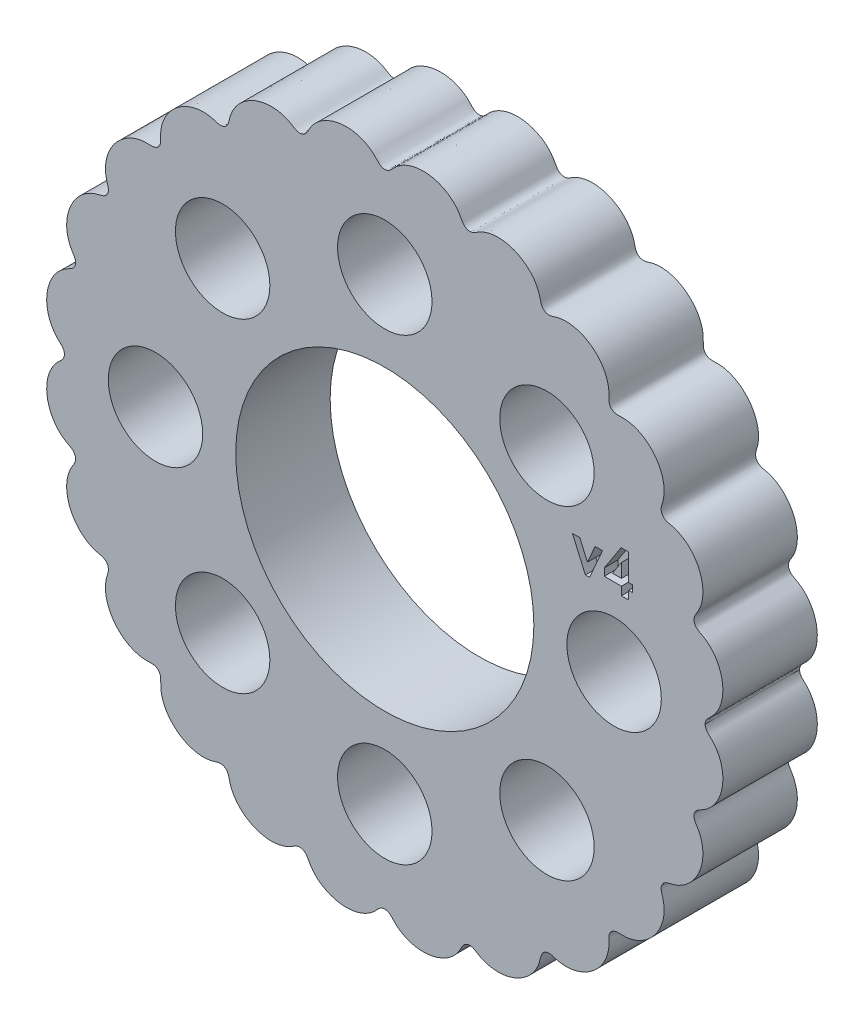
SolidWorks part; units mm, degrees
ref_plane "Plan de face" through (0, 0, 0) normal (0, 0, 1) x (1, 0, 0)
ref_plane "Plan de dessus" through (0, 0, 0) normal (0, 1, 0) x (1, 0, 0)
ref_plane "Plan de droite" through (0, 0, 0) normal (1, 0, 0) x (0, 0, -1)
sketch "Esquisse1" plane through (0, 0, 0) normal (0, 0, 1) x (1, 0, 0)
  line L0 (-1000, 0) -> (49000, 0) construction
  spline S0 degree 4 poles (22.9955, 6.6042) (22.9643, 6.5397) (22.914, 6.4032) (22.9023, 6.1862) (23.0214, 5.9244) (23.2219, 5.7605) (23.4288, 5.659) (23.6594, 5.5306) (23.9059, 5.3649) (24.1666, 5.1353) (24.4254, 4.835) (24.6422, 4.5029) (24.8162, 4.1468) (24.946, 3.7722) (25.0308, 3.385) (25.0698, 2.9906) (25.0624, 2.5943) (25.0079, 2.2017) (24.9068, 1.8224) (24.7781, 1.5066) (24.64, 1.2523) (24.5081, 1.0548) (24.3917, 0.9046) (24.2647, 0.7631) (24.1289, 0.6302) (24.012, 0.5251) (23.9248, 0.4355) (23.8688, 0.3622) (23.8363, 0.3122) (23.8082, 0.2597) (23.7852, 0.2044) (23.7697, 0.1547) (23.76, 0.1121) (23.7533, 0.0661) (23.7501, 0.0228) (23.7495, -0.004) (23.7513, -0.04) (23.7542, -0.0715) (23.7595, -0.1093) (23.7688, -0.1512) (23.7835, -0.1997) (23.8056, -0.2538) (23.8324, -0.3054) (23.8635, -0.3546) (23.9194, -0.4297) (24.009, -0.5227) (24.1313, -0.6322) (24.2737, -0.7721) (24.4392, -0.959) (24.6145, -1.2025) (24.7855, -1.5135) (24.9316, -1.8961) (25.0271, -2.299) (25.0708, -2.7153) (25.0622, -3.1311) (25.0033, -3.5401) (24.8958, -3.9363) (24.7419, -4.314) (24.5445, -4.6645) (24.307, -4.9822) (24.0331, -5.2614) (23.7654, -5.4667) (23.5164, -5.6129) (23.2956, -5.7243) (23.1195, -5.8363) (22.9763, -6.0087) (22.9044, -6.234) (22.925, -6.462) (23.0164, -6.6581) (23.1266, -6.8267) (23.2244, -6.9889) (23.3341, -7.1984) (23.4412, -7.4619) (23.5336, -7.7957) (23.5876, -8.2004) (23.5865, -8.623) (23.5267, -9.0558) (23.3808, -9.5868) (23.1436, -10.0885) (22.8209, -10.5434) (22.4327, -10.9196) (22.1006, -11.1627) (21.7948, -11.3267) (21.5321, -11.4304) (21.3065, -11.4954) (21.1232, -11.5381) (20.9306, -11.5808) (20.7385, -11.6689) (20.5325, -11.8672) (20.4495, -12.16) (20.5219, -12.4298) (20.6167, -12.7241) (20.6818, -13.0067) (20.7176, -13.3406) (20.7046, -13.7295) (20.6405, -14.1156) (20.5273, -14.4945) (20.3673, -14.8595) (20.1602, -15.2112) (19.9061, -15.5428) (19.6059, -15.8469) (19.261, -16.115) (18.8955, -16.3273) (18.5181, -16.4829) (18.1828, -16.5697) (17.9011, -16.6087) (17.6647, -16.6185) (17.4754, -16.6149) (17.2743, -16.6037) (17.0588, -16.6226) (16.851, -16.7187) (16.6918, -16.8937) (16.6141, -17.104) (16.6052, -17.3124) (16.6191, -17.5593) (16.617, -17.8481) (16.5731, -18.1826) (16.4683, -18.5594) (16.3118, -18.9239) (16.107, -19.2701) (15.8569, -19.5923) (15.5674, -19.8834) (15.2427, -20.1389) (14.8869, -20.3543) (14.5046, -20.5246) (14.1078, -20.6433) (13.7035, -20.7081) (13.2985, -20.7166) (12.9508, -20.673) (12.6603, -20.5981) (12.4161, -20.517) (12.2029, -20.4723) (11.9744, -20.5019) (11.768, -20.6211) (11.6281, -20.8042) (11.5602, -21.0112) (11.5084, -21.2632) (11.428, -21.5523) (11.2919, -21.8752) (11.082, -22.2216) (10.8237, -22.5394) (10.5226, -22.8236) (10.1839, -23.0696) (9.8195, -23.2701) (9.4358, -23.4235) (9.039, -23.5286) (8.6349, -23.5841) (8.2327, -23.5884) (7.8388, -23.5416) (7.4601, -23.444) (7.1484, -23.3148) (6.8973, -23.1723) (6.6904, -23.0367) (6.5054, -22.9402) (6.2844, -22.9024) (6.0534, -22.9528) (5.8662, -23.0846) (5.7421, -23.2618) (5.6512, -23.4416) (5.5596, -23.6073) (5.4331, -23.8072) (5.2584, -24.0316) (5.0155, -24.2786) (4.6921, -24.5276) (4.2308, -24.7924) (3.7121, -24.9769) (3.1672, -25.0695) (2.6142, -25.0665) (2.1723, -25.0046) (1.7597, -24.8871) (1.3831, -24.721) (1.0882, -24.5382) (0.867, -24.3625) (0.6979, -24.1997) (0.5693, -24.0623) (0.436, -23.9168) (0.2637, -23.7945) (-0.011, -23.7153) (-0.3061, -23.7898) (-0.5036, -23.9874) (-0.7111, -24.2166) (-0.9232, -24.4143) (-1.1945, -24.6122) (-1.5378, -24.7955) (-1.9042, -24.933) (-2.289, -25.0244) (-2.6851, -25.0684) (-3.0932, -25.0648) (-3.5074, -25.0106) (-3.9209, -24.9026) (-4.3256, -24.738) (-4.6921, -24.5276) (-5.0155, -24.2786) (-5.2584, -24.0316) (-5.4331, -23.8072) (-5.5596, -23.6073) (-5.6512, -23.4416) (-5.7421, -23.2618) (-5.8662, -23.0846) (-6.0534, -22.9528) (-6.2844, -22.9024) (-6.5054, -22.9402) (-6.6904, -23.0367) (-6.8973, -23.1723) (-7.1484, -23.3148) (-7.4601, -23.444) (-7.8388, -23.5416) (-8.2327, -23.5884) (-8.6349, -23.5841) (-9.039, -23.5286) (-9.4358, -23.4235) (-9.8195, -23.2701) (-10.1839, -23.0696) (-10.5226, -22.8236) (-10.8237, -22.5394) (-11.082, -22.2216) (-11.2919, -21.8752) (-11.428, -21.5523) (-11.5084, -21.2632) (-11.5602, -21.0112) (-11.6281, -20.8042) (-11.768, -20.6211) (-11.9744, -20.5019) (-12.2029, -20.4723) (-12.4161, -20.517) (-12.6603, -20.5981) (-12.9508, -20.673) (-13.2985, -20.7166) (-13.7035, -20.7081) (-14.1078, -20.6433) (-14.6048, -20.4946) (-15.1642, -20.2163) (-15.6552, -19.8308) (-16.055, -19.3579) (-16.3118, -18.9239) (-16.4683, -18.5594) (-16.5731, -18.1826) (-16.617, -17.8481) (-16.6191, -17.5593) (-16.6052, -17.3124) (-16.6141, -17.104) (-16.6918, -16.8937) (-16.851, -16.7187) (-17.0588, -16.6226) (-17.2743, -16.6037) (-17.4754, -16.6149) (-17.6647, -16.6185) (-17.9011, -16.6087) (-18.1828, -16.5697) (-18.5181, -16.4829) (-18.8955, -16.3273) (-19.261, -16.1151) (-19.6059, -15.8469) (-19.9061, -15.5428) (-20.1602, -15.2112) (-20.3673, -14.8595) (-20.5273, -14.4945) (-20.6405, -14.1156) (-20.7046, -13.7294) (-20.7175, -13.3407) (-20.6818, -13.0066) (-20.6166, -12.7243) (-20.522, -12.4295) (-20.4494, -12.1605) (-20.5243, -11.8962) (-20.683, -11.7227) (-20.8176, -11.632) (-20.958, -11.5755) (-21.1234, -11.5373) (-21.3064, -11.4958) (-21.5321, -11.4302) (-21.7948, -11.3268) (-22.1006, -11.1626) (-22.4327, -10.9196) (-22.7408, -10.6211) (-23.0153, -10.2693) (-23.2393, -9.8862) (-23.4104, -9.4792) (-23.5267, -9.0558) (-23.5865, -8.623) (-23.5876, -8.2004) (-23.5336, -7.7957) (-23.4412, -7.4619) (-23.3341, -7.1984) (-23.2244, -6.9889) (-23.1266, -6.8267) (-23.0164, -6.6581) (-22.925, -6.462) (-22.9044, -6.234) (-22.9763, -6.0087) (-23.1195, -5.8363) (-23.2956, -5.7243) (-23.5164, -5.6129) (-23.7654, -5.4667) (-24.0331, -5.2614) (-24.307, -4.9822) (-24.5445, -4.6645) (-24.7419, -4.314) (-24.8958, -3.9363) (-25.0033, -3.5401) (-25.0622, -3.1311) (-25.0708, -2.7153) (-25.0271, -2.299) (-24.9316, -1.8961) (-24.7855, -1.5135) (-24.6145, -1.2025) (-24.4393, -0.959) (-24.2737, -0.7721) (-24.1313, -0.6321) (-23.9982, -0.5131) (-23.8995, -0.4084) (-23.8391, -0.3182) (-23.8055, -0.2539) (-23.7835, -0.1997) (-23.7688, -0.1512) (-23.7595, -0.1093) (-23.7542, -0.0715) (-23.7513, -0.04) (-23.7495, -0.0037) (-23.7502, 0.0234) (-23.7534, 0.0677) (-23.7604, 0.1144) (-23.7705, 0.1578) (-23.7867, 0.2087) (-23.8107, 0.2649) (-23.8399, 0.3183) (-23.8736, 0.369) (-23.9317, 0.4432) (-24.0215, 0.5339) (-24.141, 0.6413) (-24.279, 0.7779) (-24.4075, 0.9235) (-24.5249, 1.0783) (-24.6575, 1.2816) (-24.7976, 1.5478) (-24.9275, 1.8824) (-25.0256, 2.2876) (-25.071, 2.7111) (-25.0623, 3.1368) (-25.0002, 3.5582) (-24.8859, 3.9683) (-24.7199, 4.3608) (-24.4999, 4.7349) (-24.2231, 5.0813) (-23.9331, 5.3469) (-23.6469, 5.5411) (-23.3456, 5.7009) (-23.0735, 5.8417) (-22.8982, 6.1368) (-22.9147, 6.4027) (-22.9638, 6.54) (-22.9956, 6.6042) knots 0 0 0 0 0 0.002762 0.005524 0.008057 0.010589 0.012487 0.014385 0.018181 0.021977 0.025773 0.029569 0.033366 0.037162 0.040959 0.044755 0.048552 0.052348 0.056144 0.059791 0.061614 0.063437 0.06526 0.067083 0.068906 0.070729 0.071301 0.071873 0.072445 0.073016 0.073588 0.07416 0.074446 0.074731 0.075303 0.075582 0.075861 0.07614 0.076419 0.076977 0.077535 0.078093 0.078652 0.07921 0.079768 0.081683 0.083599 0.085515 0.08743 0.091261 0.095093 0.099101 0.103109 0.107118 0.111126 0.115032 0.118938 0.122843 0.126749 0.130438 0.134127 0.137815 0.13966 0.141504 0.143638 0.145771 0.148068 0.150364 0.15218 0.153996 0.155812 0.157628 0.16126 0.164892 0.169075 0.173257 0.177439 0.181621 0.190162 0.194433 0.198704 0.20231 0.205917 0.20772 0.209523 0.211327 0.21313 0.215313 0.217496 0.222107 0.223949 0.225791 0.229476 0.23316 0.236844 0.240662 0.24448 0.248298 0.252116 0.256299 0.260481 0.264663 0.268845 0.272477 0.276109 0.277925 0.279741 0.281557 0.283373 0.28567 0.287966 0.2901 0.292233 0.294078 0.295922 0.299611 0.3033 0.306988 0.310894 0.3148 0.318706 0.322612 0.32662 0.330628 0.334637 0.338645 0.342476 0.346307 0.350139 0.352054 0.35397 0.356202 0.358434 0.360667 0.362899 0.364815 0.36673 0.370561 0.374393 0.378224 0.382232 0.386241 0.390249 0.394257 0.398163 0.402069 0.405975 0.40988 0.413569 0.417258 0.420947 0.422791 0.424635 0.426769 0.428902 0.431199 0.433495 0.435311 0.437127 0.438943 0.440759 0.444392 0.448024 0.452206 0.456388 0.464752 0.469023 0.473294 0.477564 0.481835 0.485441 0.489048 0.490851 0.492655 0.494458 0.496261 0.498444 0.500627 0.505239 0.507081 0.508923 0.512607 0.516291 0.519975 0.523793 0.527611 0.53143 0.535248 0.53943 0.543612 0.547794 0.551976 0.555609 0.559241 0.561057 0.562873 0.564689 0.566505 0.568801 0.571098 0.573231 0.575365 0.577209 0.579053 0.582742 0.586431 0.59012 0.594025 0.597931 0.601837 0.605743 0.609751 0.61376 0.617768 0.621776 0.625607 0.629439 0.63327 0.635186 0.637101 0.639333 0.641566 0.643798 0.64603 0.647946 0.649861 0.653693 0.657524 0.661355 0.665364 0.669372 0.677388 0.6852 0.689106 0.693012 0.6967 0.700389 0.704078 0.705922 0.707767 0.7099 0.712034 0.71433 0.716627 0.718443 0.720259 0.722075 0.723891 0.727523 0.731155 0.735337 0.739519 0.743701 0.747884 0.751702 0.75552 0.759338 0.763156 0.76684 0.770525 0.774209 0.776051 0.777893 0.782504 0.784687 0.785779 0.78687 0.788673 0.790477 0.79228 0.794083 0.79769 0.801296 0.805567 0.809838 0.814108 0.818379 0.822561 0.826743 0.830926 0.835108 0.83874 0.842372 0.844188 0.846004 0.84782 0.849636 0.851932 0.854229 0.856362 0.858496 0.86034 0.862185 0.865873 0.869562 0.873251 0.877157 0.881063 0.884968 0.888874 0.892882 0.896891 0.900899 0.904907 0.908739 0.91257 0.914486 0.916401 0.918317 0.920232 0.921349 0.921907 0.922465 0.923023 0.923581 0.92386 0.924139 0.924418 0.924697 0.925281 0.925573 0.925865 0.926449 0.927033 0.927617 0.928201 0.928785 0.929369 0.931232 0.933095 0.934957 0.93682 0.938683 0.940546 0.944272 0.94835 0.952428 0.956506 0.960584 0.964661 0.968739 0.972817 0.976894 0.98129 0.985685 0.987883 0.99008 0.994476 0.997238 1 1 1 1 1 construction
  spline S1 degree 4 poles (23.75, 0) (23.75, -0.0062) (23.7502, -0.0186) (23.7513, -0.04) (23.7542, -0.0715) (23.7595, -0.1093) (23.7688, -0.1512) (23.7835, -0.1997) (23.8056, -0.2538) (23.8324, -0.3054) (23.8635, -0.3546) (23.9194, -0.4297) (24.009, -0.5227) (24.1313, -0.6322) (24.2737, -0.7721) (24.4392, -0.959) (24.6145, -1.2025) (24.7855, -1.5135) (24.9316, -1.8961) (25.0271, -2.299) (25.0708, -2.7153) (25.0622, -3.1311) (25.0033, -3.5401) (24.8958, -3.9363) (24.7419, -4.314) (24.5445, -4.6645) (24.307, -4.9822) (24.0331, -5.2614) (23.7654, -5.4667) (23.5164, -5.6129) (23.2956, -5.7243) (23.1195, -5.8363) (22.9763, -6.0087) (22.9044, -6.234) (22.925, -6.462) (23.0164, -6.6581) (23.1266, -6.8267) (23.2244, -6.9889) (23.3341, -7.1984) (23.4412, -7.4619) (23.5336, -7.7957) (23.5876, -8.2004) (23.5865, -8.623) (23.5267, -9.0558) (23.3808, -9.5868) (23.1436, -10.0885) (22.8209, -10.5434) (22.4327, -10.9196) (22.1006, -11.1627) (21.7948, -11.3267) (21.5321, -11.4304) (21.3065, -11.4954) (21.1232, -11.5381) (20.9306, -11.5808) (20.7385, -11.6689) (20.5325, -11.8672) (20.4495, -12.16) (20.5219, -12.4298) (20.6167, -12.7241) (20.6818, -13.0067) (20.7176, -13.3406) (20.7046, -13.7295) (20.6405, -14.1156) (20.5273, -14.4945) (20.3673, -14.8595) (20.1602, -15.2112) (19.9061, -15.5428) (19.6059, -15.8469) (19.261, -16.115) (18.8955, -16.3273) (18.5181, -16.4829) (18.1828, -16.5697) (17.9011, -16.6087) (17.6647, -16.6185) (17.4754, -16.6149) (17.2743, -16.6037) (17.0588, -16.6226) (16.851, -16.7187) (16.6918, -16.8937) (16.6141, -17.104) (16.6052, -17.3124) (16.6191, -17.5593) (16.617, -17.8481) (16.5731, -18.1826) (16.4683, -18.5594) (16.3118, -18.9239) (16.107, -19.2701) (15.8569, -19.5923) (15.5674, -19.8834) (15.2427, -20.1389) (14.8869, -20.3543) (14.5046, -20.5246) (14.1078, -20.6433) (13.7035, -20.7081) (13.2985, -20.7166) (12.9508, -20.673) (12.6603, -20.5981) (12.4161, -20.517) (12.2029, -20.4723) (11.9744, -20.5019) (11.768, -20.6211) (11.6281, -20.8042) (11.5602, -21.0112) (11.5084, -21.2632) (11.428, -21.5523) (11.2919, -21.8752) (11.082, -22.2216) (10.8237, -22.5394) (10.5226, -22.8236) (10.1839, -23.0696) (9.8195, -23.2701) (9.4358, -23.4235) (9.039, -23.5286) (8.6349, -23.5841) (8.2327, -23.5884) (7.8388, -23.5416) (7.4601, -23.444) (7.1484, -23.3148) (6.8973, -23.1723) (6.6904, -23.0367) (6.5054, -22.9402) (6.2844, -22.9024) (6.0534, -22.9528) (5.8662, -23.0846) (5.7421, -23.2618) (5.6512, -23.4416) (5.5596, -23.6073) (5.4331, -23.8072) (5.2584, -24.0316) (5.0155, -24.2786) (4.6921, -24.5276) (4.2308, -24.7924) (3.7121, -24.9769) (3.1672, -25.0695) (2.6142, -25.0665) (2.1723, -25.0046) (1.7597, -24.8871) (1.3831, -24.721) (1.0882, -24.5382) (0.867, -24.3625) (0.6979, -24.1997) (0.5693, -24.0623) (0.436, -23.9168) (0.2637, -23.7945) (-0.011, -23.7153) (-0.3061, -23.7898) (-0.5036, -23.9874) (-0.7111, -24.2166) (-0.9232, -24.4143) (-1.1945, -24.6122) (-1.5378, -24.7955) (-1.9042, -24.933) (-2.289, -25.0244) (-2.6851, -25.0684) (-3.0932, -25.0648) (-3.5074, -25.0106) (-3.9209, -24.9026) (-4.3256, -24.738) (-4.6921, -24.5276) (-5.0155, -24.2786) (-5.2584, -24.0316) (-5.4331, -23.8072) (-5.5596, -23.6073) (-5.6512, -23.4416) (-5.7421, -23.2618) (-5.8662, -23.0846) (-6.0534, -22.9528) (-6.2844, -22.9024) (-6.5054, -22.9402) (-6.6904, -23.0367) (-6.8973, -23.1723) (-7.1484, -23.3148) (-7.4601, -23.444) (-7.8388, -23.5416) (-8.2327, -23.5884) (-8.6349, -23.5841) (-9.039, -23.5286) (-9.4358, -23.4235) (-9.8195, -23.2701) (-10.1839, -23.0696) (-10.5226, -22.8236) (-10.8237, -22.5394) (-11.082, -22.2216) (-11.2919, -21.8752) (-11.428, -21.5523) (-11.5084, -21.2632) (-11.5602, -21.0112) (-11.6281, -20.8042) (-11.768, -20.6211) (-11.9744, -20.5019) (-12.2029, -20.4723) (-12.4161, -20.517) (-12.6603, -20.5981) (-12.9508, -20.673) (-13.2985, -20.7166) (-13.7035, -20.7081) (-14.1078, -20.6433) (-14.6048, -20.4946) (-15.1642, -20.2163) (-15.6552, -19.8308) (-16.055, -19.3579) (-16.3118, -18.9239) (-16.4683, -18.5594) (-16.5731, -18.1826) (-16.617, -17.8481) (-16.6191, -17.5593) (-16.6052, -17.3124) (-16.6141, -17.104) (-16.6918, -16.8937) (-16.851, -16.7187) (-17.0588, -16.6226) (-17.2743, -16.6037) (-17.4754, -16.6149) (-17.6647, -16.6185) (-17.9011, -16.6087) (-18.1828, -16.5697) (-18.5181, -16.4829) (-18.8955, -16.3273) (-19.261, -16.1151) (-19.6059, -15.8469) (-19.9061, -15.5428) (-20.1602, -15.2112) (-20.3673, -14.8595) (-20.5273, -14.4945) (-20.6405, -14.1156) (-20.7046, -13.7294) (-20.7175, -13.3407) (-20.6818, -13.0066) (-20.6166, -12.7243) (-20.522, -12.4295) (-20.4494, -12.1605) (-20.5243, -11.8962) (-20.683, -11.7227) (-20.8176, -11.632) (-20.958, -11.5755) (-21.1234, -11.5373) (-21.3064, -11.4958) (-21.5321, -11.4302) (-21.7948, -11.3268) (-22.1006, -11.1626) (-22.4327, -10.9196) (-22.7408, -10.6211) (-23.0153, -10.2693) (-23.2393, -9.8862) (-23.4104, -9.4792) (-23.5267, -9.0558) (-23.5865, -8.623) (-23.5876, -8.2004) (-23.5336, -7.7957) (-23.4412, -7.4619) (-23.3341, -7.1984) (-23.2244, -6.9889) (-23.1266, -6.8267) (-23.0164, -6.6581) (-22.925, -6.462) (-22.9044, -6.234) (-22.9763, -6.0087) (-23.1195, -5.8363) (-23.2956, -5.7243) (-23.5164, -5.6129) (-23.7654, -5.4667) (-24.0331, -5.2614) (-24.307, -4.9822) (-24.5445, -4.6645) (-24.7419, -4.314) (-24.8958, -3.9363) (-25.0033, -3.5401) (-25.0622, -3.1311) (-25.0708, -2.7153) (-25.0271, -2.299) (-24.9316, -1.8961) (-24.7855, -1.5135) (-24.6145, -1.2025) (-24.4393, -0.959) (-24.2737, -0.7721) (-24.1313, -0.6321) (-23.9982, -0.5131) (-23.8995, -0.4084) (-23.8391, -0.3182) (-23.8055, -0.2539) (-23.7835, -0.1997) (-23.7688, -0.1512) (-23.7595, -0.1093) (-23.7542, -0.0715) (-23.7513, -0.04) (-23.7502, -0.0186) (-23.75, -0.0062) (-23.75, 0) knots 0.075303 0.075303 0.075303 0.075303 0.075303 0.075582 0.075861 0.07614 0.076419 0.076977 0.077535 0.078093 0.078652 0.07921 0.079768 0.081683 0.083599 0.085515 0.08743 0.091261 0.095093 0.099101 0.103109 0.107118 0.111126 0.115032 0.118938 0.122843 0.126749 0.130438 0.134127 0.137815 0.13966 0.141504 0.143638 0.145771 0.148068 0.150364 0.15218 0.153996 0.155812 0.157628 0.16126 0.164892 0.169075 0.173257 0.177439 0.181621 0.190162 0.194433 0.198704 0.20231 0.205917 0.20772 0.209523 0.211327 0.21313 0.215313 0.217496 0.222107 0.223949 0.225791 0.229476 0.23316 0.236844 0.240662 0.24448 0.248298 0.252116 0.256299 0.260481 0.264663 0.268845 0.272477 0.276109 0.277925 0.279741 0.281557 0.283373 0.28567 0.287966 0.2901 0.292233 0.294078 0.295922 0.299611 0.3033 0.306988 0.310894 0.3148 0.318706 0.322612 0.32662 0.330628 0.334637 0.338645 0.342476 0.346307 0.350139 0.352054 0.35397 0.356202 0.358434 0.360667 0.362899 0.364815 0.36673 0.370561 0.374393 0.378224 0.382232 0.386241 0.390249 0.394257 0.398163 0.402069 0.405975 0.40988 0.413569 0.417258 0.420947 0.422791 0.424635 0.426769 0.428902 0.431199 0.433495 0.435311 0.437127 0.438943 0.440759 0.444392 0.448024 0.452206 0.456388 0.464752 0.469023 0.473294 0.477564 0.481835 0.485441 0.489048 0.490851 0.492655 0.494458 0.496261 0.498444 0.500627 0.505239 0.507081 0.508923 0.512607 0.516291 0.519975 0.523793 0.527611 0.53143 0.535248 0.53943 0.543612 0.547794 0.551976 0.555609 0.559241 0.561057 0.562873 0.564689 0.566505 0.568801 0.571098 0.573231 0.575365 0.577209 0.579053 0.582742 0.586431 0.59012 0.594025 0.597931 0.601837 0.605743 0.609751 0.61376 0.617768 0.621776 0.625607 0.629439 0.63327 0.635186 0.637101 0.639333 0.641566 0.643798 0.64603 0.647946 0.649861 0.653693 0.657524 0.661355 0.665364 0.669372 0.677388 0.6852 0.689106 0.693012 0.6967 0.700389 0.704078 0.705922 0.707767 0.7099 0.712034 0.71433 0.716627 0.718443 0.720259 0.722075 0.723891 0.727523 0.731155 0.735337 0.739519 0.743701 0.747884 0.751702 0.75552 0.759338 0.763156 0.76684 0.770525 0.774209 0.776051 0.777893 0.782504 0.784687 0.785779 0.78687 0.788673 0.790477 0.79228 0.794083 0.79769 0.801296 0.805567 0.809838 0.814108 0.818379 0.822561 0.826743 0.830926 0.835108 0.83874 0.842372 0.844188 0.846004 0.84782 0.849636 0.851932 0.854229 0.856362 0.858496 0.86034 0.862185 0.865873 0.869562 0.873251 0.877157 0.881063 0.884968 0.888874 0.892882 0.896891 0.900899 0.904907 0.908739 0.91257 0.914486 0.916401 0.918317 0.920232 0.921349 0.921907 0.922465 0.923023 0.923581 0.92386 0.924139 0.924418 0.924697 0.924697 0.924697 0.924697 0.924697 construction
  spline S2 degree 4 poles (23.75, 0) (23.75, 0.0062) (23.7502, 0.0186) (23.7513, 0.04) (23.7542, 0.0715) (23.7595, 0.1093) (23.7688, 0.1512) (23.7835, 0.1997) (23.8056, 0.2538) (23.8324, 0.3054) (23.8635, 0.3546) (23.9194, 0.4297) (24.009, 0.5227) (24.1313, 0.6322) (24.2737, 0.7721) (24.4392, 0.959) (24.6145, 1.2025) (24.7855, 1.5135) (24.9316, 1.8961) (25.0271, 2.299) (25.0708, 2.7153) (25.0622, 3.1311) (25.0033, 3.5401) (24.8958, 3.9363) (24.7419, 4.314) (24.5445, 4.6645) (24.307, 4.9822) (24.0331, 5.2614) (23.7654, 5.4667) (23.5164, 5.6129) (23.2956, 5.7243) (23.1195, 5.8363) (22.9763, 6.0087) (22.9044, 6.234) (22.925, 6.462) (23.0164, 6.6581) (23.1266, 6.8267) (23.2244, 6.9889) (23.3341, 7.1984) (23.4412, 7.4619) (23.5336, 7.7957) (23.5876, 8.2004) (23.5865, 8.623) (23.5267, 9.0558) (23.3808, 9.5868) (23.1436, 10.0885) (22.8209, 10.5434) (22.4327, 10.9196) (22.1006, 11.1627) (21.7948, 11.3267) (21.5321, 11.4304) (21.3065, 11.4954) (21.1232, 11.5381) (20.9306, 11.5808) (20.7385, 11.6689) (20.5325, 11.8672) (20.4495, 12.16) (20.5219, 12.4298) (20.6167, 12.7241) (20.6818, 13.0067) (20.7176, 13.3406) (20.7046, 13.7295) (20.6405, 14.1156) (20.5273, 14.4945) (20.3673, 14.8595) (20.1602, 15.2112) (19.9061, 15.5428) (19.6059, 15.8469) (19.261, 16.115) (18.8955, 16.3273) (18.5181, 16.4829) (18.1828, 16.5697) (17.9011, 16.6087) (17.6647, 16.6185) (17.4754, 16.6149) (17.2743, 16.6037) (17.0588, 16.6226) (16.851, 16.7187) (16.6918, 16.8937) (16.6141, 17.104) (16.6052, 17.3124) (16.6191, 17.5593) (16.617, 17.8481) (16.5731, 18.1826) (16.4683, 18.5594) (16.3118, 18.9239) (16.107, 19.2701) (15.8569, 19.5923) (15.5674, 19.8834) (15.2427, 20.1389) (14.8869, 20.3543) (14.5046, 20.5246) (14.1078, 20.6433) (13.7035, 20.7081) (13.2985, 20.7166) (12.9508, 20.673) (12.6603, 20.5981) (12.4161, 20.517) (12.2029, 20.4723) (11.9744, 20.5019) (11.768, 20.6211) (11.6281, 20.8042) (11.5602, 21.0112) (11.5084, 21.2632) (11.428, 21.5523) (11.2919, 21.8752) (11.082, 22.2216) (10.8237, 22.5394) (10.5226, 22.8236) (10.1839, 23.0696) (9.8195, 23.2701) (9.4358, 23.4235) (9.039, 23.5286) (8.6349, 23.5841) (8.2327, 23.5884) (7.8388, 23.5416) (7.4601, 23.444) (7.1484, 23.3148) (6.8973, 23.1723) (6.6904, 23.0367) (6.5054, 22.9402) (6.2844, 22.9024) (6.0534, 22.9528) (5.8662, 23.0846) (5.7421, 23.2618) (5.6512, 23.4416) (5.5596, 23.6073) (5.4331, 23.8072) (5.2584, 24.0316) (5.0155, 24.2786) (4.6921, 24.5276) (4.2308, 24.7924) (3.7121, 24.9769) (3.1672, 25.0695) (2.6142, 25.0665) (2.1723, 25.0046) (1.7597, 24.8871) (1.3831, 24.721) (1.0882, 24.5382) (0.867, 24.3625) (0.6979, 24.1997) (0.5693, 24.0623) (0.436, 23.9168) (0.2637, 23.7945) (-0.011, 23.7153) (-0.3061, 23.7898) (-0.5036, 23.9874) (-0.7111, 24.2166) (-0.9232, 24.4143) (-1.1945, 24.6122) (-1.5378, 24.7955) (-1.9042, 24.933) (-2.289, 25.0244) (-2.6851, 25.0684) (-3.0932, 25.0648) (-3.5074, 25.0106) (-3.9209, 24.9026) (-4.3256, 24.738) (-4.6921, 24.5276) (-5.0155, 24.2786) (-5.2584, 24.0316) (-5.4331, 23.8072) (-5.5596, 23.6073) (-5.6512, 23.4416) (-5.7421, 23.2618) (-5.8662, 23.0846) (-6.0534, 22.9528) (-6.2844, 22.9024) (-6.5054, 22.9402) (-6.6904, 23.0367) (-6.8973, 23.1723) (-7.1484, 23.3148) (-7.4601, 23.444) (-7.8388, 23.5416) (-8.2327, 23.5884) (-8.6349, 23.5841) (-9.039, 23.5286) (-9.4358, 23.4235) (-9.8195, 23.2701) (-10.1839, 23.0696) (-10.5226, 22.8236) (-10.8237, 22.5394) (-11.082, 22.2216) (-11.2919, 21.8752) (-11.428, 21.5523) (-11.5084, 21.2632) (-11.5602, 21.0112) (-11.6281, 20.8042) (-11.768, 20.6211) (-11.9744, 20.5019) (-12.2029, 20.4723) (-12.4161, 20.517) (-12.6603, 20.5981) (-12.9508, 20.673) (-13.2985, 20.7166) (-13.7035, 20.7081) (-14.1078, 20.6433) (-14.6048, 20.4946) (-15.1642, 20.2163) (-15.6552, 19.8308) (-16.055, 19.3579) (-16.3118, 18.9239) (-16.4683, 18.5594) (-16.5731, 18.1826) (-16.617, 17.8481) (-16.6191, 17.5593) (-16.6052, 17.3124) (-16.6141, 17.104) (-16.6918, 16.8937) (-16.851, 16.7187) (-17.0588, 16.6226) (-17.2743, 16.6037) (-17.4754, 16.6149) (-17.6647, 16.6185) (-17.9011, 16.6087) (-18.1828, 16.5697) (-18.5181, 16.4829) (-18.8955, 16.3273) (-19.261, 16.1151) (-19.6059, 15.8469) (-19.9061, 15.5428) (-20.1602, 15.2112) (-20.3673, 14.8595) (-20.5273, 14.4945) (-20.6405, 14.1156) (-20.7046, 13.7294) (-20.7175, 13.3407) (-20.6818, 13.0066) (-20.6166, 12.7243) (-20.522, 12.4295) (-20.4494, 12.1605) (-20.5243, 11.8962) (-20.683, 11.7227) (-20.8176, 11.632) (-20.958, 11.5755) (-21.1234, 11.5373) (-21.3064, 11.4958) (-21.5321, 11.4302) (-21.7948, 11.3268) (-22.1006, 11.1626) (-22.4327, 10.9196) (-22.7408, 10.6211) (-23.0153, 10.2693) (-23.2393, 9.8862) (-23.4104, 9.4792) (-23.5267, 9.0558) (-23.5865, 8.623) (-23.5876, 8.2004) (-23.5336, 7.7957) (-23.4412, 7.4619) (-23.3341, 7.1984) (-23.2244, 6.9889) (-23.1266, 6.8267) (-23.0164, 6.6581) (-22.925, 6.462) (-22.9044, 6.234) (-22.9763, 6.0087) (-23.1195, 5.8363) (-23.2956, 5.7243) (-23.5164, 5.6129) (-23.7654, 5.4667) (-24.0331, 5.2614) (-24.307, 4.9822) (-24.5445, 4.6645) (-24.7419, 4.314) (-24.8958, 3.9363) (-25.0033, 3.5401) (-25.0622, 3.1311) (-25.0708, 2.7153) (-25.0271, 2.299) (-24.9316, 1.8961) (-24.7855, 1.5135) (-24.6145, 1.2025) (-24.4393, 0.959) (-24.2737, 0.7721) (-24.1313, 0.6321) (-23.9982, 0.5131) (-23.8995, 0.4084) (-23.8391, 0.3182) (-23.8055, 0.2539) (-23.7835, 0.1997) (-23.7688, 0.1512) (-23.7595, 0.1093) (-23.7542, 0.0715) (-23.7513, 0.04) (-23.7502, 0.0186) (-23.75, 0.0062) (-23.75, 0) knots 0.075303 0.075303 0.075303 0.075303 0.075303 0.075582 0.075861 0.07614 0.076419 0.076977 0.077535 0.078093 0.078652 0.07921 0.079768 0.081683 0.083599 0.085515 0.08743 0.091261 0.095093 0.099101 0.103109 0.107118 0.111126 0.115032 0.118938 0.122843 0.126749 0.130438 0.134127 0.137815 0.13966 0.141504 0.143638 0.145771 0.148068 0.150364 0.15218 0.153996 0.155812 0.157628 0.16126 0.164892 0.169075 0.173257 0.177439 0.181621 0.190162 0.194433 0.198704 0.20231 0.205917 0.20772 0.209523 0.211327 0.21313 0.215313 0.217496 0.222107 0.223949 0.225791 0.229476 0.23316 0.236844 0.240662 0.24448 0.248298 0.252116 0.256299 0.260481 0.264663 0.268845 0.272477 0.276109 0.277925 0.279741 0.281557 0.283373 0.28567 0.287966 0.2901 0.292233 0.294078 0.295922 0.299611 0.3033 0.306988 0.310894 0.3148 0.318706 0.322612 0.32662 0.330628 0.334637 0.338645 0.342476 0.346307 0.350139 0.352054 0.35397 0.356202 0.358434 0.360667 0.362899 0.364815 0.36673 0.370561 0.374393 0.378224 0.382232 0.386241 0.390249 0.394257 0.398163 0.402069 0.405975 0.40988 0.413569 0.417258 0.420947 0.422791 0.424635 0.426769 0.428902 0.431199 0.433495 0.435311 0.437127 0.438943 0.440759 0.444392 0.448024 0.452206 0.456388 0.464752 0.469023 0.473294 0.477564 0.481835 0.485441 0.489048 0.490851 0.492655 0.494458 0.496261 0.498444 0.500627 0.505239 0.507081 0.508923 0.512607 0.516291 0.519975 0.523793 0.527611 0.53143 0.535248 0.53943 0.543612 0.547794 0.551976 0.555609 0.559241 0.561057 0.562873 0.564689 0.566505 0.568801 0.571098 0.573231 0.575365 0.577209 0.579053 0.582742 0.586431 0.59012 0.594025 0.597931 0.601837 0.605743 0.609751 0.61376 0.617768 0.621776 0.625607 0.629439 0.63327 0.635186 0.637101 0.639333 0.641566 0.643798 0.64603 0.647946 0.649861 0.653693 0.657524 0.661355 0.665364 0.669372 0.677388 0.6852 0.689106 0.693012 0.6967 0.700389 0.704078 0.705922 0.707767 0.7099 0.712034 0.71433 0.716627 0.718443 0.720259 0.722075 0.723891 0.727523 0.731155 0.735337 0.739519 0.743701 0.747884 0.751702 0.75552 0.759338 0.763156 0.76684 0.770525 0.774209 0.776051 0.777893 0.782504 0.784687 0.785779 0.78687 0.788673 0.790477 0.79228 0.794083 0.79769 0.801296 0.805567 0.809838 0.814108 0.818379 0.822561 0.826743 0.830926 0.835108 0.83874 0.842372 0.844188 0.846004 0.84782 0.849636 0.851932 0.854229 0.856362 0.858496 0.86034 0.862185 0.865873 0.869562 0.873251 0.877157 0.881063 0.884968 0.888874 0.892882 0.896891 0.900899 0.904907 0.908739 0.91257 0.914486 0.916401 0.918317 0.920232 0.921349 0.921907 0.922465 0.923023 0.923581 0.92386 0.924139 0.924418 0.924697 0.924697 0.924697 0.924697 0.924697 construction
  spline S3 degree 1 poles (23.75, 0) (-23.75, 0) knots 0 0 1 1 construction
  spline S4 degree 1 poles (23.75, 0) (-23.75, 0) knots 0 0 1 1 construction
  spline S5 degree 3 poles (23.75, 0) (23.75, 0.1137) (23.8219, 0.3453) (24.0779, 0.5835) (24.3269, 0.822) (24.6131, 1.1852) (24.88, 1.7) (25.0523, 2.3737) (25.0798, 3.068) (24.9658, 3.7534) (24.714, 4.4011) (24.3299, 4.981) (23.9042, 5.3758) (23.5122, 5.6193) (23.1973, 5.7658) (22.9497, 6.022) (22.891, 6.382) (23.0374, 6.7027) (23.2955, 7.0836) (23.5106, 7.6247) (23.6065, 8.3133) (23.5489, 9.0061) (23.3498, 9.6718) (23.0199, 10.2833) (22.5707, 10.8139) (22.0159, 11.233) (21.4813, 11.4634) (21.0294, 11.5505) (20.6992, 11.6737) (20.486, 11.9701) (20.4801, 12.3255) (20.599, 12.6524) (20.7041, 13.1016) (20.726, 13.6818) (20.5875, 14.3634) (20.3076, 14.9994) (19.9035, 15.5647) (19.3931, 16.0362) (18.7949, 16.3908) (18.2422, 16.566) (17.7829, 16.6205) (17.4383, 16.613) (17.0884, 16.6008) (16.7684, 16.7684) (16.6008, 17.0884) (16.6129, 17.4383) (16.6205, 17.7829) (16.566, 18.2422) (16.3908, 18.7949) (16.0362, 19.3931) (15.5647, 19.9035) (14.9995, 20.3075) (14.3634, 20.5875) (13.6817, 20.726) (13.1016, 20.7041) (12.6522, 20.5991) (12.3259, 20.48) (11.9697, 20.4861) (11.6737, 20.6992) (11.5504, 21.0295) (11.4637, 21.4813) (11.233, 22.016) (10.814, 22.5707) (10.2832, 23.0199) (9.6718, 23.3498) (9.0061, 23.5489) (8.3132, 23.6065) (7.6247, 23.5105) (7.0835, 23.2956) (6.7027, 23.0375) (6.3819, 22.8911) (6.022, 22.9497) (5.7658, 23.1973) (5.6193, 23.5123) (5.3758, 23.9042) (4.981, 24.3299) (4.4011, 24.714) (3.7534, 24.9658) (3.068, 25.0798) (2.3737, 25.0523) (1.7, 24.88) (1.1852, 24.6131) (0.822, 24.3269) (0.5834, 24.078) (0.3446, 23.8219) (0.0001, 23.714) (-0.3442, 23.8218) (-0.5845, 24.0782) (-0.8215, 24.3267) (-1.1856, 24.6132) (-1.6999, 24.88) (-2.3737, 25.0523) (-3.068, 25.0798) (-3.7534, 24.9658) (-4.4011, 24.714) (-4.981, 24.3299) (-5.3758, 23.9042) (-5.6193, 23.5123) (-5.7658, 23.1973) (-6.022, 22.9497) (-6.3819, 22.8911) (-6.7027, 23.0375) (-7.0835, 23.2956) (-7.6247, 23.5105) (-8.3132, 23.6065) (-9.0061, 23.5489) (-9.6718, 23.3498) (-10.2832, 23.0199) (-10.814, 22.5707) (-11.233, 22.016) (-11.4637, 21.4813) (-11.5504, 21.0295) (-11.6737, 20.6992) (-11.9697, 20.4861) (-12.3259, 20.48) (-12.6522, 20.5991) (-13.1016, 20.7041) (-13.6817, 20.726) (-14.3634, 20.5875) (-14.9995, 20.3075) (-15.5647, 19.9035) (-16.0362, 19.3931) (-16.3908, 18.7949) (-16.566, 18.2422) (-16.6205, 17.7829) (-16.6129, 17.4383) (-16.6008, 17.0884) (-16.7684, 16.7684) (-17.0884, 16.6008) (-17.4383, 16.613) (-17.7829, 16.6205) (-18.2422, 16.566) (-18.7949, 16.3908) (-19.3931, 16.0362) (-19.9035, 15.5647) (-20.3076, 14.9994) (-20.5875, 14.3634) (-20.726, 13.6818) (-20.7041, 13.1016) (-20.599, 12.6524) (-20.48, 12.3256) (-20.486, 11.97) (-20.6991, 11.6738) (-21.0294, 11.5505) (-21.4813, 11.4636) (-22.0159, 11.233) (-22.5707, 10.814) (-23.0199, 10.2833) (-23.3498, 9.6718) (-23.5489, 9.0061) (-23.6065, 8.3133) (-23.5106, 7.6247) (-23.2955, 7.0836) (-23.0374, 6.7027) (-22.891, 6.382) (-22.9497, 6.022) (-23.1973, 5.7658) (-23.5122, 5.6193) (-23.9042, 5.3758) (-24.3299, 4.981) (-24.714, 4.4011) (-24.9658, 3.7534) (-25.0798, 3.068) (-25.0523, 2.3737) (-24.88, 1.7) (-24.6131, 1.1852) (-24.3269, 0.822) (-24.0779, 0.5835) (-23.8219, 0.3453) (-23.75, 0.1137) (-23.75, 0) knots 0.075303 0.075303 0.075303 0.075303 0.078621 0.081939 0.085257 0.088575 0.095211 0.101847 0.108483 0.115118 0.121754 0.12839 0.135026 0.138344 0.141662 0.14498 0.148298 0.151616 0.154934 0.16157 0.168206 0.174841 0.181477 0.188113 0.194749 0.201385 0.208021 0.211339 0.214657 0.217975 0.221293 0.224611 0.227929 0.234564 0.2412 0.247836 0.254472 0.261108 0.267744 0.27438 0.277698 0.281016 0.284334 0.287652 0.29097 0.294287 0.297605 0.300923 0.307559 0.314195 0.320831 0.327467 0.334103 0.340739 0.347375 0.350693 0.35401 0.357328 0.360646 0.363964 0.367282 0.373918 0.380554 0.38719 0.393826 0.400462 0.407098 0.413733 0.420369 0.423687 0.427005 0.430323 0.433641 0.436959 0.440277 0.446913 0.453549 0.460185 0.466821 0.473456 0.480092 0.486728 0.490046 0.493364 0.496682 0.5 0.503318 0.506636 0.509954 0.513272 0.519908 0.526544 0.533179 0.539815 0.546451 0.553087 0.559723 0.563041 0.566359 0.569677 0.572995 0.576313 0.579631 0.586267 0.592902 0.599538 0.606174 0.61281 0.619446 0.626082 0.632718 0.636036 0.639354 0.642672 0.64599 0.649308 0.652625 0.659261 0.665897 0.672533 0.679169 0.685805 0.692441 0.699077 0.702395 0.705713 0.709031 0.712348 0.715666 0.718984 0.722302 0.72562 0.732256 0.738892 0.745528 0.752164 0.7588 0.765436 0.772071 0.775389 0.778707 0.782025 0.785343 0.788661 0.791979 0.798615 0.805251 0.811887 0.818523 0.825159 0.831794 0.83843 0.845066 0.848384 0.851702 0.85502 0.858338 0.861656 0.864974 0.87161 0.878246 0.884882 0.891518 0.898153 0.904789 0.911425 0.914743 0.918061 0.921379 0.924697 0.924697 0.924697 0.924697
  spline S6 degree 3 poles (-23.75, 0) (-23.75, -0.1137) (-23.8219, -0.3453) (-24.0779, -0.5835) (-24.3269, -0.822) (-24.6131, -1.1852) (-24.88, -1.7) (-25.0523, -2.3737) (-25.0798, -3.068) (-24.9658, -3.7534) (-24.714, -4.4011) (-24.3299, -4.981) (-23.9042, -5.3758) (-23.5122, -5.6193) (-23.1973, -5.7658) (-22.9497, -6.022) (-22.891, -6.382) (-23.0374, -6.7027) (-23.2955, -7.0836) (-23.5106, -7.6247) (-23.6065, -8.3133) (-23.5489, -9.0061) (-23.3498, -9.6718) (-23.0199, -10.2833) (-22.5707, -10.814) (-22.0159, -11.233) (-21.4813, -11.4636) (-21.0294, -11.5505) (-20.6991, -11.6738) (-20.486, -11.97) (-20.48, -12.3256) (-20.599, -12.6524) (-20.7041, -13.1016) (-20.726, -13.6818) (-20.5875, -14.3634) (-20.3076, -14.9994) (-19.9035, -15.5647) (-19.3931, -16.0362) (-18.7949, -16.3908) (-18.2422, -16.566) (-17.7829, -16.6205) (-17.4383, -16.613) (-17.0884, -16.6008) (-16.7684, -16.7684) (-16.6008, -17.0884) (-16.6129, -17.4383) (-16.6205, -17.7829) (-16.566, -18.2422) (-16.3908, -18.7949) (-16.0362, -19.3931) (-15.5647, -19.9035) (-14.9995, -20.3075) (-14.3634, -20.5875) (-13.6817, -20.726) (-13.1016, -20.7041) (-12.6522, -20.5991) (-12.3259, -20.48) (-11.9697, -20.4861) (-11.6737, -20.6992) (-11.5504, -21.0295) (-11.4637, -21.4813) (-11.233, -22.016) (-10.814, -22.5707) (-10.2832, -23.0199) (-9.6718, -23.3498) (-9.0061, -23.5489) (-8.3132, -23.6065) (-7.6247, -23.5105) (-7.0835, -23.2956) (-6.7027, -23.0375) (-6.3819, -22.8911) (-6.022, -22.9497) (-5.7658, -23.1973) (-5.6193, -23.5123) (-5.3758, -23.9042) (-4.981, -24.3299) (-4.4011, -24.714) (-3.7534, -24.9658) (-3.068, -25.0798) (-2.3737, -25.0523) (-1.6999, -24.88) (-1.1856, -24.6132) (-0.8215, -24.3267) (-0.5845, -24.0782) (-0.3442, -23.8218) (0.0001, -23.714) (0.3446, -23.8219) (0.5834, -24.078) (0.822, -24.3269) (1.1852, -24.6131) (1.7, -24.88) (2.3737, -25.0523) (3.068, -25.0798) (3.7534, -24.9658) (4.4011, -24.714) (4.981, -24.3299) (5.3758, -23.9042) (5.6193, -23.5123) (5.7658, -23.1973) (6.022, -22.9497) (6.3819, -22.8911) (6.7027, -23.0375) (7.0835, -23.2956) (7.6247, -23.5105) (8.3132, -23.6065) (9.0061, -23.5489) (9.6718, -23.3498) (10.2832, -23.0199) (10.814, -22.5707) (11.233, -22.016) (11.4637, -21.4813) (11.5504, -21.0295) (11.6737, -20.6992) (11.9697, -20.4861) (12.3259, -20.48) (12.6522, -20.5991) (13.1016, -20.7041) (13.6817, -20.726) (14.3634, -20.5875) (14.9995, -20.3075) (15.5647, -19.9035) (16.0362, -19.3931) (16.3908, -18.7949) (16.566, -18.2422) (16.6205, -17.7829) (16.6129, -17.4383) (16.6008, -17.0884) (16.7684, -16.7684) (17.0884, -16.6008) (17.4383, -16.613) (17.7829, -16.6205) (18.2422, -16.566) (18.7949, -16.3908) (19.3931, -16.0362) (19.9035, -15.5647) (20.3076, -14.9994) (20.5875, -14.3634) (20.726, -13.6818) (20.7041, -13.1016) (20.599, -12.6524) (20.4801, -12.3255) (20.486, -11.9701) (20.6992, -11.6737) (21.0294, -11.5505) (21.4813, -11.4634) (22.0159, -11.233) (22.5707, -10.8139) (23.0199, -10.2833) (23.3498, -9.6718) (23.5489, -9.0061) (23.6065, -8.3133) (23.5106, -7.6247) (23.2955, -7.0836) (23.0374, -6.7027) (22.891, -6.382) (22.9497, -6.022) (23.1973, -5.7658) (23.5122, -5.6193) (23.9042, -5.3758) (24.3299, -4.981) (24.714, -4.4011) (24.9658, -3.7534) (25.0798, -3.068) (25.0523, -2.3737) (24.88, -1.7) (24.6131, -1.1852) (24.3269, -0.822) (24.0779, -0.5835) (23.8219, -0.3453) (23.75, -0.1137) (23.75, 0) knots 0.075303 0.075303 0.075303 0.075303 0.078621 0.081939 0.085257 0.088575 0.095211 0.101847 0.108483 0.115118 0.121754 0.12839 0.135026 0.138344 0.141662 0.14498 0.148298 0.151616 0.154934 0.16157 0.168206 0.174841 0.181477 0.188113 0.194749 0.201385 0.208021 0.211339 0.214657 0.217975 0.221293 0.224611 0.227929 0.234564 0.2412 0.247836 0.254472 0.261108 0.267744 0.27438 0.277698 0.281016 0.284334 0.287652 0.29097 0.294287 0.297605 0.300923 0.307559 0.314195 0.320831 0.327467 0.334103 0.340739 0.347375 0.350693 0.35401 0.357328 0.360646 0.363964 0.367282 0.373918 0.380554 0.38719 0.393826 0.400462 0.407098 0.413733 0.420369 0.423687 0.427005 0.430323 0.433641 0.436959 0.440277 0.446913 0.453549 0.460185 0.466821 0.473456 0.480092 0.486728 0.490046 0.493364 0.496682 0.5 0.503318 0.506636 0.509954 0.513272 0.519908 0.526544 0.533179 0.539815 0.546451 0.553087 0.559723 0.563041 0.566359 0.569677 0.572995 0.576313 0.579631 0.586267 0.592902 0.599538 0.606174 0.61281 0.619446 0.626082 0.632718 0.636036 0.639354 0.642672 0.64599 0.649308 0.652625 0.659261 0.665897 0.672533 0.679169 0.685805 0.692441 0.699077 0.702395 0.705713 0.709031 0.712348 0.715666 0.718984 0.722302 0.72562 0.732256 0.738892 0.745528 0.752164 0.7588 0.765436 0.772071 0.775389 0.778707 0.782025 0.785343 0.788661 0.791979 0.798615 0.805251 0.811887 0.818523 0.825159 0.831794 0.83843 0.845066 0.848384 0.851702 0.85502 0.858338 0.861656 0.864974 0.87161 0.878246 0.884882 0.891518 0.898153 0.904789 0.911425 0.914743 0.918061 0.921379 0.924697 0.924697 0.924697 0.924697
  dimension "D2" = 0
extrude "Boss.-Extru.1" add sketch "Esquisse1" along normal blind 7
sketch "Esquisse2" plane through (0, 0, 7) normal (0, 0, 1) x (1, 0, 0)
  circle A0 centre (0, 0) radius 11.05
  circle A1 centre (0, 17) radius 3.5
  circle A2 centre (12.0208, 12.0208) radius 3.5
  circle A3 centre (17, 0) radius 3.5
  circle A4 centre (12.0208, -12.0208) radius 3.5
  circle A5 centre (0, -17) radius 3.5
  circle A6 centre (-12.0208, -12.0208) radius 3.5
  circle A7 centre (-17, 0) radius 3.5
  circle A8 centre (-12.0208, 12.0208) radius 3.5
  point P15 (0, 0)
  dimension "D1" = 22.1
  dimension "D2" = 7
  dimension "D3" = 17
  dimension "D4" = 8
extrude "Enlèv. mat.-Extru.1" cut sketch "Esquisse2" against normal through all
sketch "Esquisse3" plane through (0, 0, 7) normal (0, 0, 1) x (1, 0, 0)
  text T0 "<b>v4</b>" font "Century Gothic" height 3
extrude "Version Text" cut sketch "Esquisse3" against normal blind 1
equation "\"R\"= 25'Radius of the rotor"
equation "\"E\"= 0.75'Eccentricity from input shaft to center of rotor"
equation "\"Rr\"= 0.5'Roller radius"
equation "\"N\"= 25'Amount of rollers"
